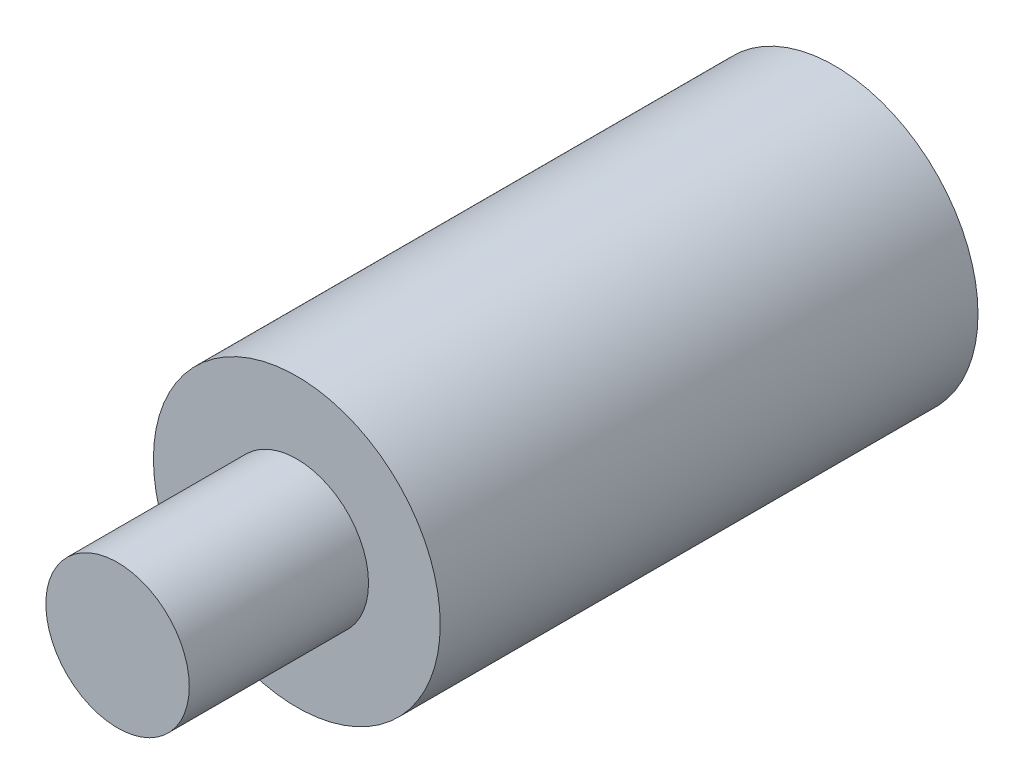
SolidWorks part; units mm, degrees
ref_plane "Front Plane" through (0, 0, 0) normal (0, 0, 1) x (1, 0, 0)
ref_plane "Top Plane" through (0, 0, 0) normal (0, 1, 0) x (1, 0, 0)
ref_plane "Right Plane" through (0, 0, 0) normal (1, 0, 0) x (0, 0, -1)
sketch "Sketch1" plane through (0, 0, 0) normal (0, 0, 1) x (1, 0, 0)
  circle A0 centre (0, 0) radius 4
  dimension "D1" = 8
extrude "Boss-Extrude1" add sketch "Sketch1" along normal blind 15
sketch "Sketch2" plane through (0, 0, 15) normal (0, 0, 1) x (1, 0, 0)
  circle A0 centre (0, 0) radius 2
  dimension "D1" = 4
extrude "Boss-Extrude2" add sketch "Sketch2" along normal blind 5
sketch "Sketch3" plane through (0, 0, 0) normal (0, 0, -1) x (-1, 0, 0)
  circle A0 centre (0, 0) radius 1.5
  dimension "D1" = 3
extrude "Cut-Extrude1" cut sketch "Sketch3" against normal blind 10
cosmetic thread "Cosmetic Thread2" parameters "D1"=8, "D2"=4
